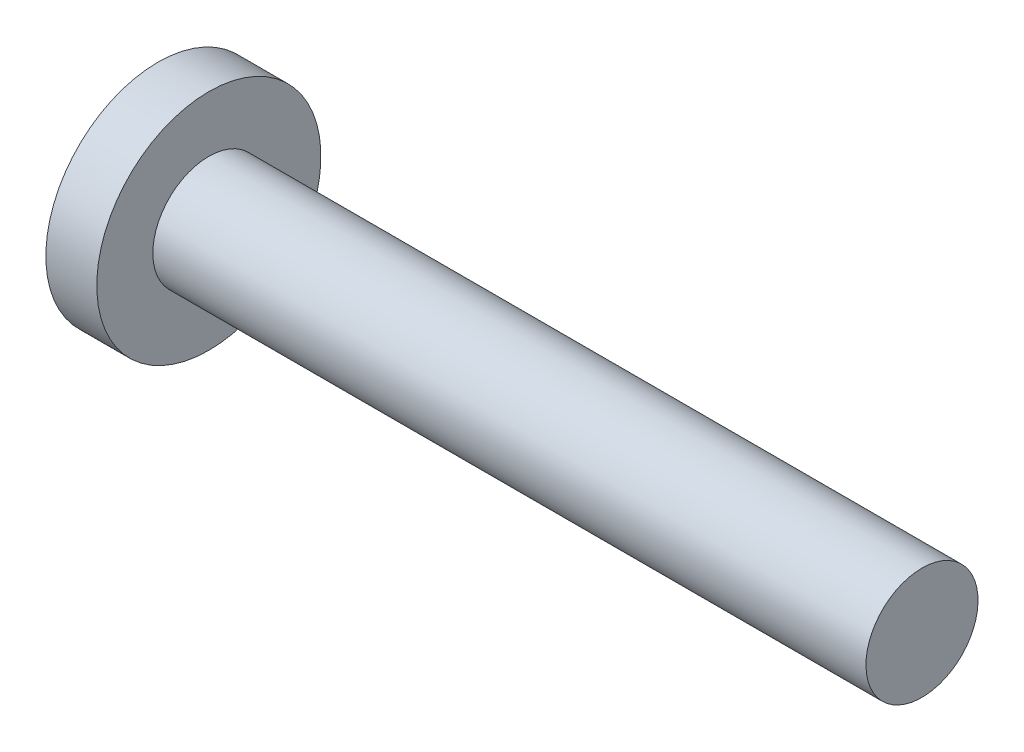
SolidWorks part; units mm, degrees
ref_plane "Front Plane" through (0, 0, 0) normal (0, 0, 1) x (1, 0, 0)
ref_plane "Top Plane" through (0, 0, 0) normal (0, 1, 0) x (1, 0, 0)
ref_plane "Right Plane" through (0, 0, 0) normal (1, 0, 0) x (0, 0, -1)
sketch "Sketch4" plane through (0, 0, 0) normal (0, 0, 1) x (1, 0, 0)
  line L0 (0, 0) -> (0, 22)
  line L1 (0, 22) -> (10, 22)
  line L2 (10, 22) -> (10, 11)
  line L3 (10, 11) -> (150, 11)
  line L4 (150, 11) -> (150, 0)
  line L5 (150, 0) -> (0, 0)
  dimension "D1" = 11
  dimension "D2" = 22
  dimension "D3" = 10
  dimension "D4" = 150
revolve "Revolve1" add sketch "Sketch4" angle 360 about L5
